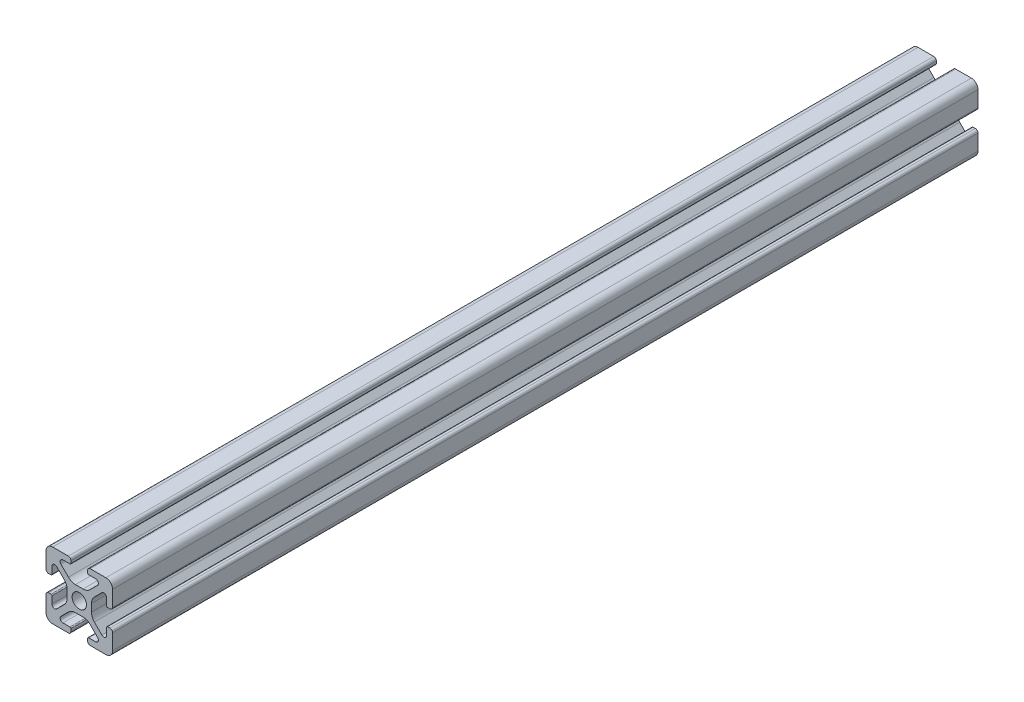
SolidWorks part; units mm, degrees
material "Alliage 1060"
ref_plane "Plan de face" through (0, 0, 0) normal (0, 0, 1) x (1, 0, 0)
ref_plane "Plan de dessus" through (0, 0, 0) normal (0, 1, 0) x (1, 0, 0)
ref_plane "Plan de droite" through (0, 0, 0) normal (1, 0, 0) x (0, 0, -1)
sketch "Esquisse1" plane through (0, 0, 0) normal (0, 0, 1) x (1, 0, 0)
  line L108 (-3.2559, 4.5287) -> (-5.5062, 6.779)
  line L109 (-4.9176, 8.2) -> (-2.8, 8.2)
  line L110 (-2.5, 8.5) -> (-2.5, 9.2)
  line L111 (-3.3, 10) -> (-8, 10)
  line L112 (-10, 8) -> (-10, 3.3)
  line L113 (-9.2, 2.5) -> (-8.5, 2.5)
  line L114 (-8.2, 2.8) -> (-8.2, 4.9176)
  line L115 (-6.779, 5.5062) -> (-4.5287, 3.2559)
  line L116 (-3.65, 1.1346) -> (-3.65, -1.1346)
  line L117 (-4.5287, -3.2559) -> (-6.779, -5.5062)
  line L118 (-8.2, -4.9176) -> (-8.2, -2.8)
  line L119 (-8.5, -2.5) -> (-9.2, -2.5)
  line L120 (-10, -3.3) -> (-10, -8)
  line L121 (-8, -10) -> (-3.3, -10)
  line L122 (-2.5, -9.2) -> (-2.5, -8.5)
  line L123 (-2.8, -8.2) -> (-4.9176, -8.2)
  line L124 (-5.5062, -6.779) -> (-3.2559, -4.5287)
  line L125 (-1.1346, -3.65) -> (1.1346, -3.65)
  line L126 (3.2559, -4.5287) -> (5.5062, -6.779)
  line L127 (4.9176, -8.2) -> (2.8, -8.2)
  line L128 (2.5, -8.5) -> (2.5, -9.2)
  line L129 (3.3, -10) -> (8, -10)
  line L130 (10, -8) -> (10, -3.3)
  line L131 (9.2, -2.5) -> (8.5, -2.5)
  line L132 (8.2, -2.8) -> (8.2, -4.9176)
  line L133 (6.779, -5.5062) -> (4.5287, -3.2559)
  line L134 (3.65, -1.1346) -> (3.65, 1.1346)
  line L135 (4.5287, 3.2559) -> (6.779, 5.5062)
  line L136 (8.2, 4.9176) -> (8.2, 2.8)
  line L137 (8.5, 2.5) -> (9.2, 2.5)
  line L138 (10, 3.3) -> (10, 8)
  line L139 (8, 10) -> (3.3, 10)
  line L140 (2.5, 9.2) -> (2.5, 8.5)
  line L141 (2.8, 8.2) -> (4.9176, 8.2)
  line L142 (5.5062, 6.779) -> (3.2559, 4.5287)
  line L143 (1.1346, 3.65) -> (-1.1346, 3.65)
  arc A42 (-2.15, 0) -> (2.15, 0) centre (0, 0) ccw
  arc A43 (2.15, 0) -> (-2.15, 0) centre (0, 0) ccw
  arc A108 (-4.9176, 8.2) -> (-5.5062, 6.779) centre (-4.9176, 7.3676) ccw
  arc A109 (-2.8, 8.2) -> (-2.5, 8.5) centre (-2.8, 8.5) ccw
  arc A110 (-2.5, 9.2) -> (-3.3, 10) centre (-3.3, 9.2) ccw
  arc A111 (-8, 10) -> (-10, 8) centre (-8, 8) ccw
  arc A112 (-10, 3.3) -> (-9.2, 2.5) centre (-9.2, 3.3) ccw
  arc A113 (-8.5, 2.5) -> (-8.2, 2.8) centre (-8.5, 2.8) ccw
  arc A114 (-6.779, 5.5062) -> (-8.2, 4.9176) centre (-7.3676, 4.9176) ccw
  arc A115 (-3.65, 1.1346) -> (-4.5287, 3.2559) centre (-6.65, 1.1346) ccw
  arc A116 (-4.5287, -3.2559) -> (-3.65, -1.1346) centre (-6.65, -1.1346) ccw
  arc A117 (-8.2, -4.9176) -> (-6.779, -5.5062) centre (-7.3676, -4.9176) ccw
  arc A118 (-8.2, -2.8) -> (-8.5, -2.5) centre (-8.5, -2.8) ccw
  arc A119 (-9.2, -2.5) -> (-10, -3.3) centre (-9.2, -3.3) ccw
  arc A120 (-10, -8) -> (-8, -10) centre (-8, -8) ccw
  arc A121 (-3.3, -10) -> (-2.5, -9.2) centre (-3.3, -9.2) ccw
  arc A122 (-2.5, -8.5) -> (-2.8, -8.2) centre (-2.8, -8.5) ccw
  arc A123 (-5.5062, -6.779) -> (-4.9176, -8.2) centre (-4.9176, -7.3676) ccw
  arc A124 (-1.1346, -3.65) -> (-3.2559, -4.5287) centre (-1.1346, -6.65) ccw
  arc A125 (3.2559, -4.5287) -> (1.1346, -3.65) centre (1.1346, -6.65) ccw
  arc A126 (4.9176, -8.2) -> (5.5062, -6.779) centre (4.9176, -7.3676) ccw
  arc A127 (2.8, -8.2) -> (2.5, -8.5) centre (2.8, -8.5) ccw
  arc A128 (2.5, -9.2) -> (3.3, -10) centre (3.3, -9.2) ccw
  arc A129 (8, -10) -> (10, -8) centre (8, -8) ccw
  arc A130 (10, -3.3) -> (9.2, -2.5) centre (9.2, -3.3) ccw
  arc A131 (8.5, -2.5) -> (8.2, -2.8) centre (8.5, -2.8) ccw
  arc A132 (6.779, -5.5062) -> (8.2, -4.9176) centre (7.3676, -4.9176) ccw
  arc A133 (3.65, -1.1346) -> (4.5287, -3.2559) centre (6.65, -1.1346) ccw
  arc A134 (4.5287, 3.2559) -> (3.65, 1.1346) centre (6.65, 1.1346) ccw
  arc A135 (8.2, 4.9176) -> (6.779, 5.5062) centre (7.3676, 4.9176) ccw
  arc A136 (8.2, 2.8) -> (8.5, 2.5) centre (8.5, 2.8) ccw
  arc A137 (9.2, 2.5) -> (10, 3.3) centre (9.2, 3.3) ccw
  arc A138 (10, 8) -> (8, 10) centre (8, 8) ccw
  arc A139 (3.3, 10) -> (2.5, 9.2) centre (3.3, 9.2) ccw
  arc A140 (2.5, 8.5) -> (2.8, 8.2) centre (2.8, 8.5) ccw
  arc A141 (5.5062, 6.779) -> (4.9176, 8.2) centre (4.9176, 7.3676) ccw
  arc A142 (1.1346, 3.65) -> (3.2559, 4.5287) centre (1.1346, 6.65) ccw
  arc A143 (-3.2559, 4.5287) -> (-1.1346, 3.65) centre (-1.1346, 6.65) ccw
extrude "Boss.-Extru.1" add sketch "Esquisse1" along normal blind 260
